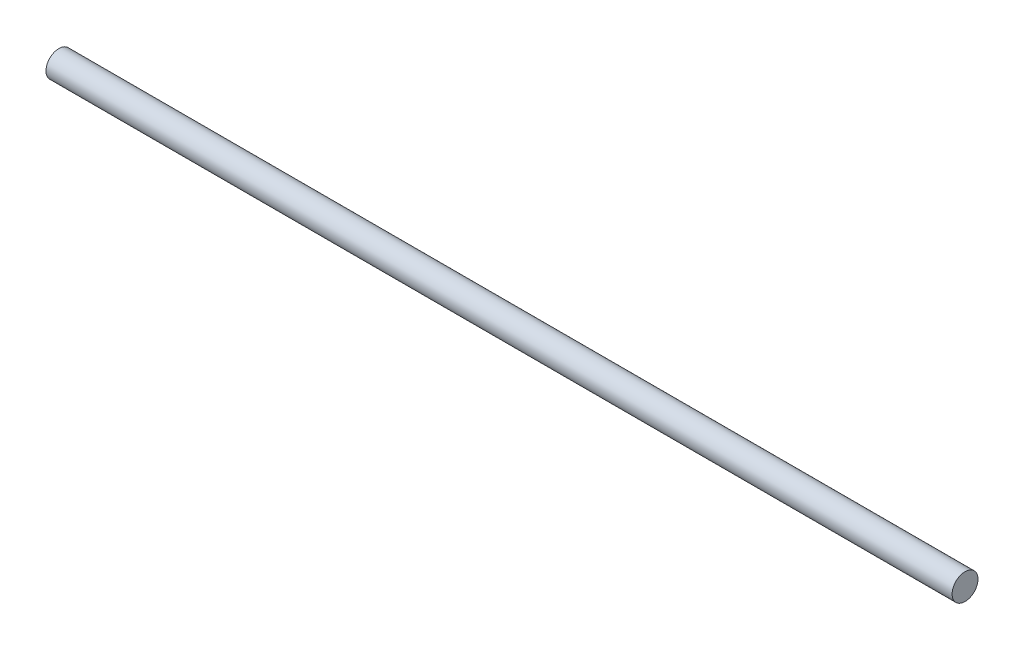
SolidWorks part; units mm, degrees
material "1060 合金"
ref_plane "前视基准面" through (0, 0, 0) normal (0, 0, 1) x (1, 0, 0)
ref_plane "上视基准面" through (0, 0, 0) normal (0, 1, 0) x (1, 0, 0)
ref_plane "右视基准面" through (0, 0, 0) normal (1, 0, 0) x (0, 0, -1)
sketch "草图1" plane through (0, 0, 0) normal (1, 0, 0) x (0, 0, -1)
  circle A0 centre (-8.755, 16.6527) radius 2.4293
extrude "凸台-拉伸1" add sketch "草图1" along normal blind 170
